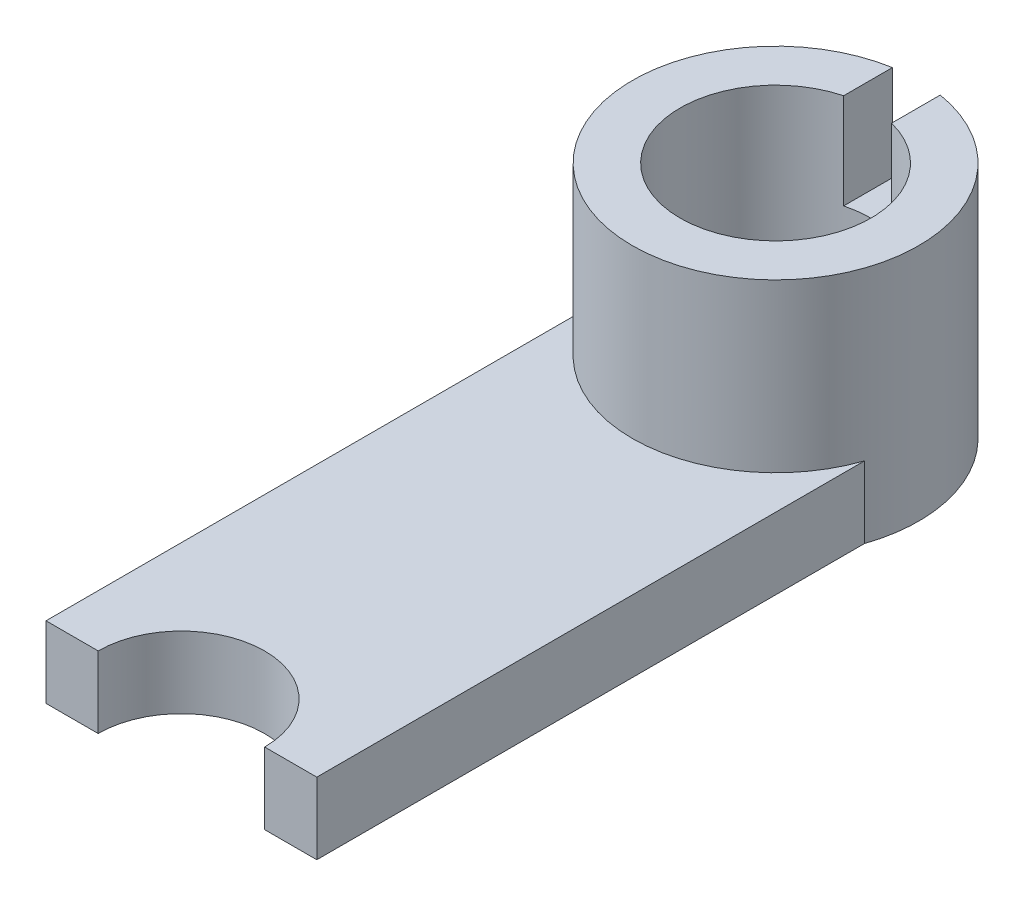
SolidWorks part; units mm, degrees
material "Cast Alloy Steel"
ref_plane "Front Plane" through (0, 0, 0) normal (0, 0, 1) x (1, 0, 0)
ref_plane "Top Plane" through (0, 0, 0) normal (0, 1, 0) x (1, 0, 0)
ref_plane "Right Plane" through (0, 0, 0) normal (1, 0, 0) x (0, 0, -1)
sketch "Sketch2" plane through (0, 0, 0) normal (0, 1, 0) x (1, 0, 0)
  circle A0 centre (0, 0) radius 40000
  circle A1 centre (0, 0) radius 60000
extrude "Boss-Extrude1" add sketch "Sketch2" along normal blind 100000
sketch "Sketch3" plane through (0, 100000, 0) normal (0, 1, 0) x (1, 0, 0)
  line L1 (-10166.3729, 61934.6879) -> (9833.6271, 61934.6879)
  line L2 (-10166.3729, 61934.6879) -> (-10166.3729, 8183.4176)
  line L3 (-10166.3729, 8183.4176) -> (9833.6271, 8183.4176)
  line L4 (9833.6271, 61934.6879) -> (9833.6271, 8183.4176)
  line L5 (-10166.3729, 61934.6879) -> (9833.6271, 8183.4176) construction
  line L6 (-10166.3729, 8183.4176) -> (9833.6271, 61934.6879) construction
  point P0 (-166.3729, 35059.0527)
  dimension "D1" = 20000
extrude "Cut-Extrude1" cut sketch "Sketch3" against normal blind 40000 and the other way blind 14630
sketch "Sketch6" plane through (0, 0, 0) normal (0, -1, 0) x (1, 0, 0)
  line L1 (56743.8198, 249016.177) -> (-56743.8198, 249016.177)
  line L2 (56743.8198, 249016.177) -> (56743.8198, 19497.1514)
  line L3 (56743.8198, 19497.1514) -> (-56743.8198, 19497.1514)
  line L4 (-56743.8198, 249016.177) -> (-56743.8198, 19497.1514)
  line L5 (56743.8198, 249016.177) -> (-56743.8198, 19497.1514) construction
  line L6 (56743.8198, 19497.1514) -> (-56743.8198, 249016.177) construction
  circle A0 centre (0, 0) radius 60000 construction
  point P0 (0, 134256.6642)
extrude "Boss-Extrude3" add sketch "Sketch6" against normal blind 30000
sketch "Sketch7" plane through (0, 30000, 0) normal (0, 1, 0) x (1, 0, 0)
  line L0 (56743.8198, -249016.177) -> (-56743.8198, -249016.177) construction
  circle A0 centre (0, -249016.177) radius 34880.8875
extrude "Cut-Extrude2" cut sketch "Sketch7" against normal blind 58994 and the other way blind 28505
sketch "Sketch8" plane through (0, 30000, 0) normal (0, 1, 0) x (1, 0, 0)
  circle A0 centre (0, 0) radius 40000
extrude "Cut-Extrude4" cut sketch "Sketch8" against normal blind 76239 and the other way blind 51190
